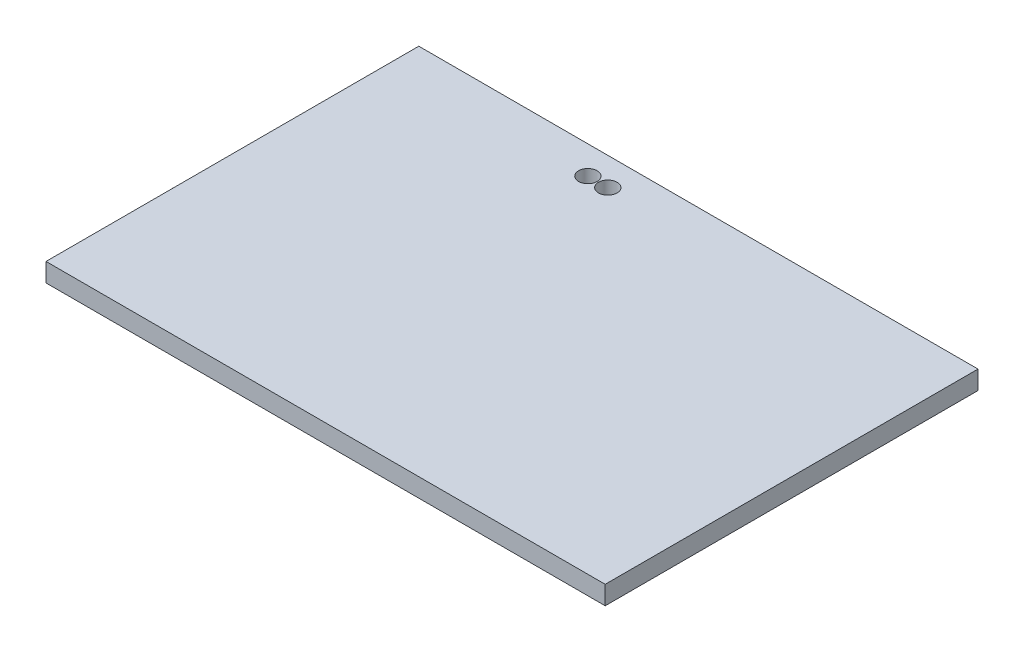
SolidWorks part; units mm, degrees
ref_plane "Alzado" through (0, 0, 0) normal (0, 0, 1) x (1, 0, 0)
ref_plane "Planta" through (0, 0, 0) normal (0, 1, 0) x (1, 0, 0)
ref_plane "Vista lateral" through (0, 0, 0) normal (1, 0, 0) x (0, 0, -1)
sketch "Croquis1" plane through (0, 0, 0) normal (0, 1, 0) x (1, 0, 0)
  line L1 (-150, -100) -> (150, -100)
  line L2 (-150, -100) -> (-150, 100)
  line L3 (-150, 100) -> (150, 100)
  line L4 (150, -100) -> (150, 100)
  line L5 (-150, -100) -> (150, 100) construction
  line L6 (-150, 100) -> (150, -100) construction
  point P0 (0, 0)
  dimension "D1" = 300
  dimension "D2" = 200
extrude "Saliente-Extruir1" add sketch "Croquis1" along normal blind 10
sketch "Croquis2" plane through (0, 10, 0) normal (0, 1, 0) x (1, 0, 0)
  circle A0 centre (-44.281, 85) radius 5
  circle A1 centre (-33.6107, 85) radius 5
extrude "Cortar-Extruir2" cut sketch "Croquis2" against normal up to surface (10 mm away) up to face at (0, 0, 0)
